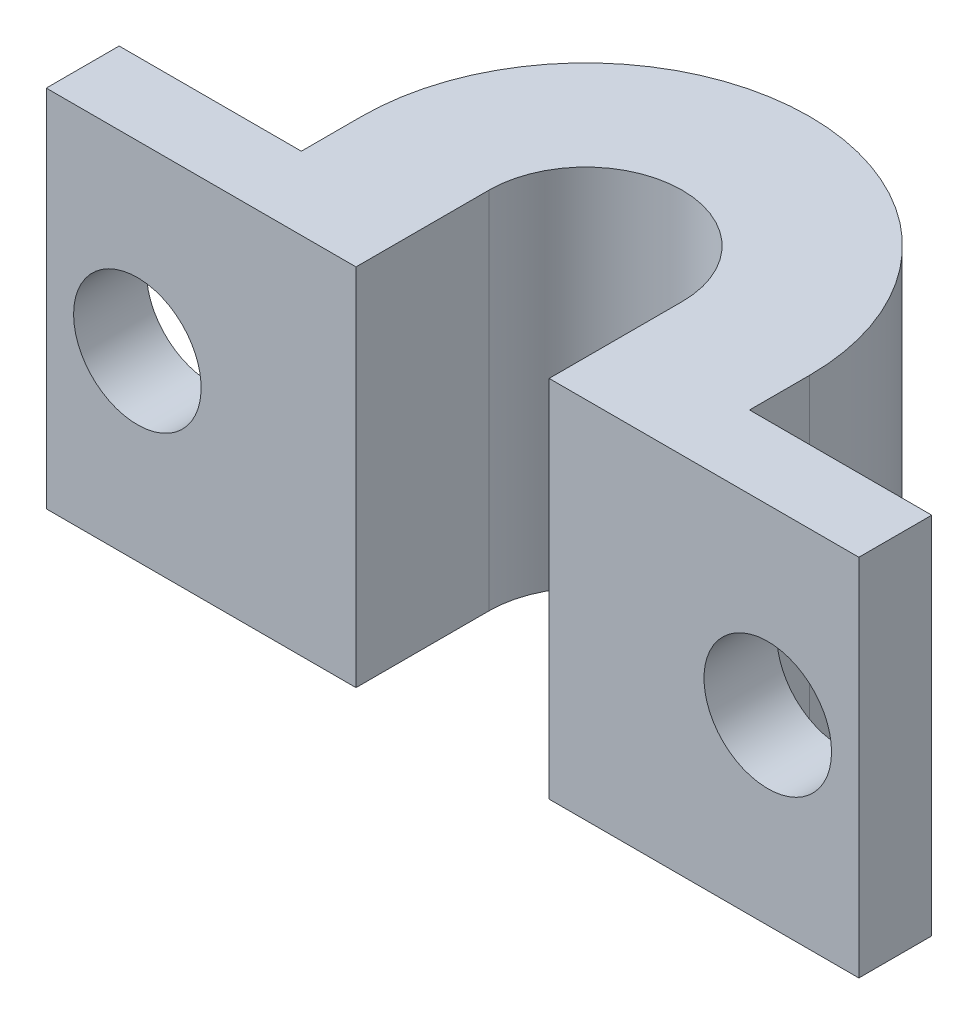
SolidWorks part; units mm, degrees
ref_plane "前视基准面" through (0, 0, 0) normal (0, 0, 1) x (1, 0, 0)
ref_plane "上视基准面" through (0, 0, 0) normal (0, 1, 0) x (1, 0, 0)
ref_plane "右视基准面" through (0, 0, 0) normal (1, 0, 0) x (0, 0, -1)
other "Configuration Table"
sketch "草图1" plane through (0, 0, 0) normal (0, 1, 0) x (1, 0, 0)
  line L2 (-6.15, 0) -> (-6.15, -1.65)
  line L3 (0, 2.65) -> (0, -0.102) construction
  line L4 (2.65, 0) -> (2.65, -2.65)
  line L5 (-2.65, 0) -> (-2.65, -2.65)
  line L6 (6.15, 0) -> (6.15, -1.65)
  line L7 (-2.65, -2.65) -> (-2.65, -3.65)
  line L8 (-2.65, 0) -> (-2.65, -2.65)
  line L10 (-6.15, -3.65) -> (-2.65, -3.65)
  line L11 (6.15, -3.65) -> (2.65, -3.65)
  line L13 (2.65, -2.65) -> (2.65, -3.65)
  line L14 (-6.15, -1.65) -> (-11.15, -1.65)
  line L15 (-11.15, -1.65) -> (-11.15, -3.65)
  line L16 (-11.15, -3.65) -> (-6.15, -3.65)
  line L17 (11.15, -3.65) -> (6.15, -3.65)
  line L18 (6.15, -1.65) -> (11.15, -1.65)
  line L19 (11.15, -1.65) -> (11.15, -3.65)
  arc A0 (2.65, 0) -> (-2.65, 0) centre (0, 0) ccw
  arc A1 (6.15, 0) -> (-6.15, 0) centre (0, 0) ccw
  circle A2 centre (0, 0) radius 6.15 construction
  circle A3 centre (0, 0) radius 2.65 construction
  arc A4 (2.65, 0) -> (-2.65, 0) centre (0, 0) ccw
  point P14 (0, -2.65)
  dimension "D1" = 5.3
  dimension "D3" = 5.3
  dimension "D4" = 2.65
  dimension "D5" = 1
  dimension "D6" = 5
  dimension "D7" = 2
  dimension "D2" = 3.5
extrude "凸台-拉伸1" add sketch "草图1" along normal blind 10 contours L6 A1 L2 L14 L15 L16 L10 L7 L5 A0 L4 L13 L11 L17 L19 L18
sketch "草图2" plane through (0, 0, 1.65) normal (0, 0, -1) x (-1, 0, 0)
  line L0 (11.15, 10) -> (11.15, 0) construction
  line L1 (6.15, 10) -> (11.15, 10) construction
  line L2 (8.65, 10) -> (8.65, 5) construction
  line L3 (8.65, 5) -> (11.15, 5) construction
  line L4 (0, 0) -> (0, 10) construction
  line L5 (6.15, 10) -> (-6.15, 10) construction
  line L6 (-8.65, 10) -> (-8.65, 5) construction
  line L7 (-8.65, 5) -> (-11.15, 5) construction
  circle A0 centre (8.65, 5) radius 1.75
  circle A1 centre (-8.65, 5) radius 1.75
  point P0 (11.15, 5)
  point P1 (8.65, 10)
  point P19 (-11.15, 5)
  dimension "D1" = 3.5
extrude "切除-拉伸1" cut sketch "草图2" against normal blind 10
